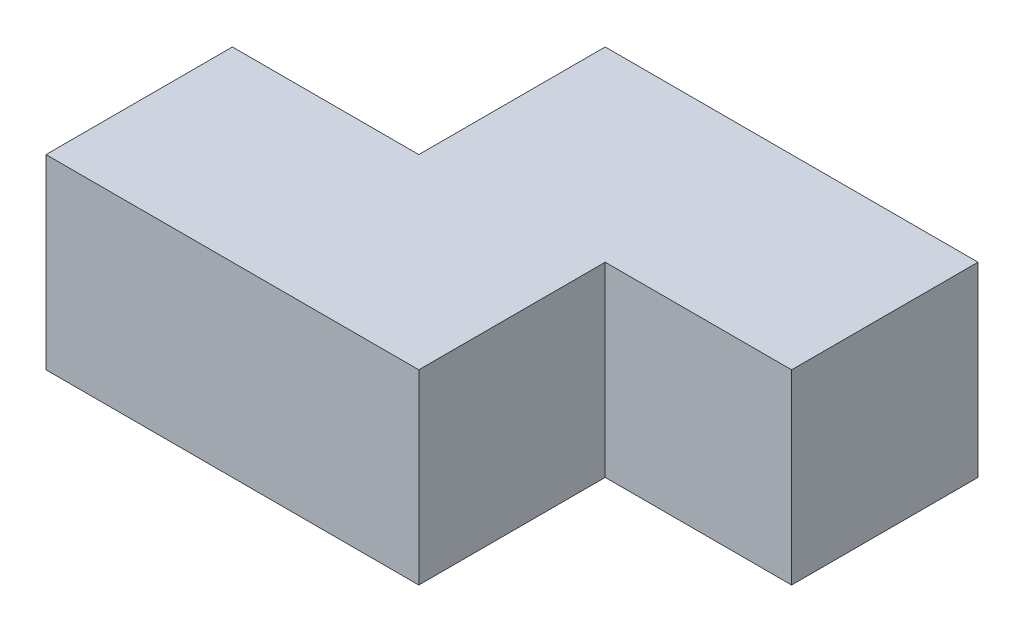
SolidWorks part; units mm, degrees
material "Oak"
ref_plane "Front Plane" through (0, 0, 0) normal (0, 0, 1) x (1, 0, 0)
ref_plane "Top Plane" through (0, 0, 0) normal (0, 1, 0) x (1, 0, 0)
ref_plane "Right Plane" through (0, 0, 0) normal (1, 0, 0) x (0, 0, -1)
sketch "Sketch1" plane through (0, 0, 0) normal (0, 1, 0) x (1, 0, 0)
  line L0 (0, 0) -> (0, 30)
  line L1 (0, 30) -> (30, 30)
  line L2 (30, 30) -> (30, 60)
  line L3 (30, 60) -> (90, 60)
  line L4 (90, 60) -> (90, 30)
  line L5 (90, 30) -> (60, 30)
  line L6 (60, 30) -> (60, 0)
  line L7 (60, 0) -> (0, 0)
  point P9 (0, 0)
  dimension "D1" = 30
  dimension "D2" = 30
  dimension "D3" = 60
  dimension "D4" = 30
  dimension "D5" = 90
  dimension "D6" = 60
  dimension "D7" = 30
extrude "Boss-Extrude1" add sketch "Sketch1" along normal blind 30
